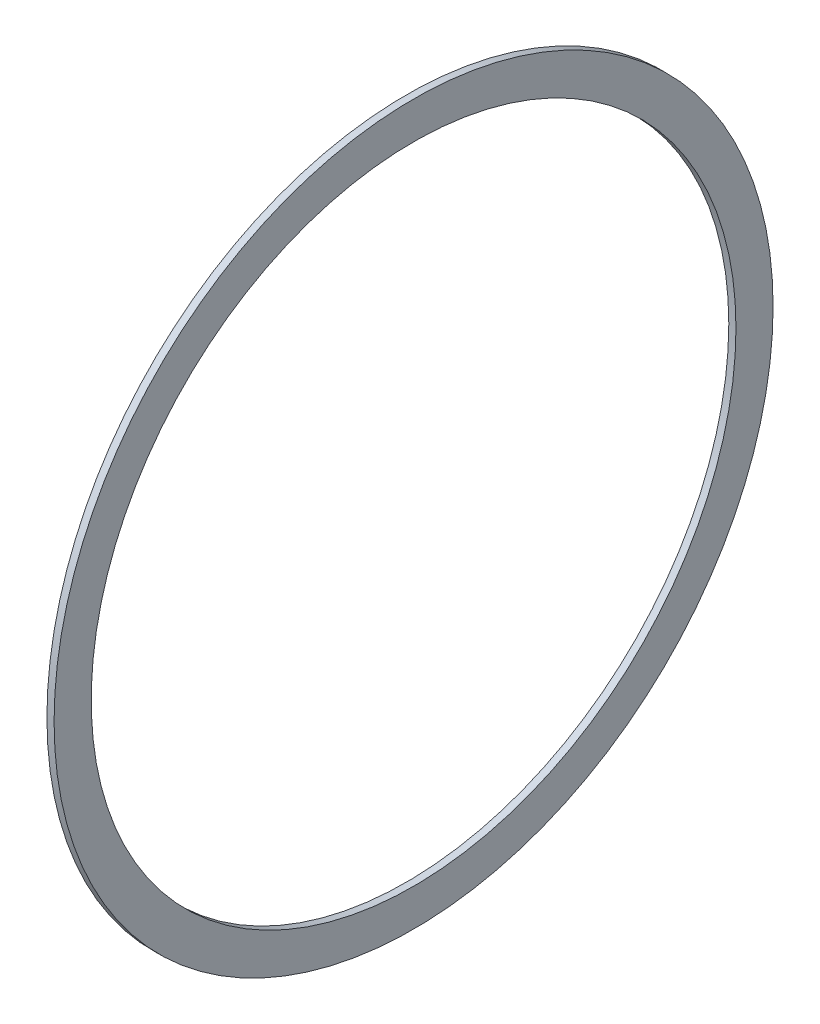
SolidWorks part; units mm, degrees
material "AISI 316 Stainless Steel Sheet (SS)"
ref_plane "Front Plane" through (0, 0, 0) normal (0, 0, 1) x (1, 0, 0)
ref_plane "Top Plane" through (0, 0, 0) normal (0, 1, 0) x (1, 0, 0)
ref_plane "Right Plane" through (0, 0, 0) normal (1, 0, 0) x (0, 0, -1)
sketch "Sketch1" plane through (0, 0, 0) normal (1, 0, 0) x (0, 0, -1)
  circle A0 centre (0, 0) radius 76.2
  circle A1 centre (0, 0) radius 68.3311
  dimension "D1" = 152.4
  dimension "D2" = 136.6622
extrude "Boss-Extrude1" add sketch "Sketch1" along normal blind 1.5189
